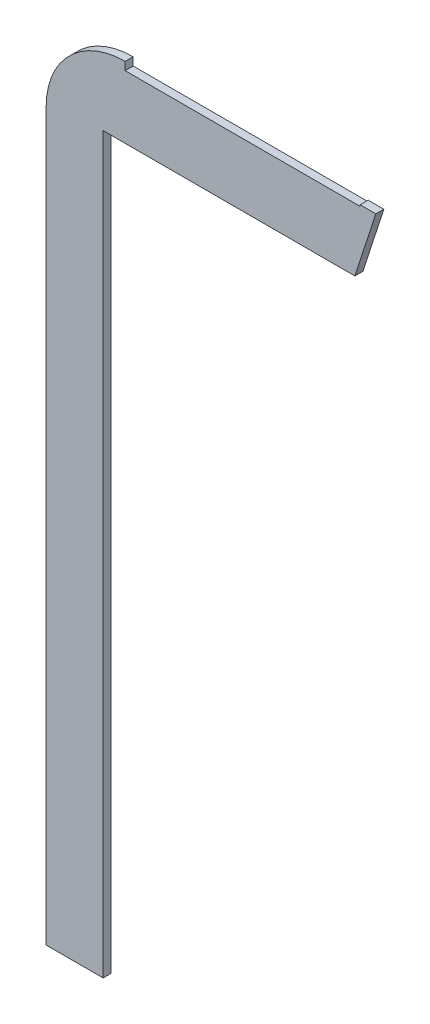
SolidWorks part; units mm, degrees
ref_plane "Front Plane" through (0, 0, 0) normal (0, 0, 1) x (1, 0, 0)
ref_plane "Top Plane" through (0, 0, 0) normal (0, 1, 0) x (1, 0, 0)
ref_plane "Right Plane" through (0, 0, 0) normal (1, 0, 0) x (0, 0, -1)
sketch "Sketch1" plane through (0, 0, 0) normal (0, 0, 1) x (1, 0, 0)
  line L0 (93.9783, 269) -> (0, 269)
  line L1 (0, 269) -> (0, -5)
  line L2 (0, 266) -> (0, -10) construction
  line L4 (0, -5) -> (-21.3, -5)
  line L5 (-21.3, -5) -> (-21.3, 266)
  line L6 (95.9381, 293) -> (3.9641, 293)
  line L9 (95.9381, 293) -> (101.8043, 293)
  line L10 (101.8043, 293) -> (93.9783, 269)
  circle A0 centre (8.2003, 266) radius 29.5003
extrude "Boss-Extrude1" add sketch "Sketch1" along normal blind 3
sketch "Sketch2" plane through (0, 0, 3) normal (0, 0, 1) x (1, 0, 0)
  line L0 (8.1995, 295.5003) -> (95.9381, 295.5003)
  line L1 (95.9381, 296) -> (95.9381, 293) construction
  line L2 (95.9381, 295.5003) -> (95.9381, 293)
  line L3 (20.0861, 293) -> (101.8043, 293) construction
  line L4 (95.9381, 293) -> (8.805, 293)
  line L5 (8.805, 293) -> (8.1995, 295.5003)
  arc A0 (20.0861, 293) -> (-21.3, 266) centre (8.2003, 266) ccw construction
extrude "Boss-Extrude2" add sketch "Sketch2" against normal blind 3
sketch "Sketch3" plane through (0, 0, 0) normal (0, 0, -1) x (-1, 0, 0)
  line L0 (-8.2003, 295.5003) -> (-8.2003, 292.5)
  line L1 (-8.2003, 292.5) -> (-95.9381, 292.5)
  line L2 (-8.2003, 295.5003) -> (-95.9381, 295.5003)
  line L3 (-95.9381, 295.5003) -> (-95.9381, 292.5)
extrude "Cut-Extrude1" cut sketch "Sketch3" against normal blind 300
